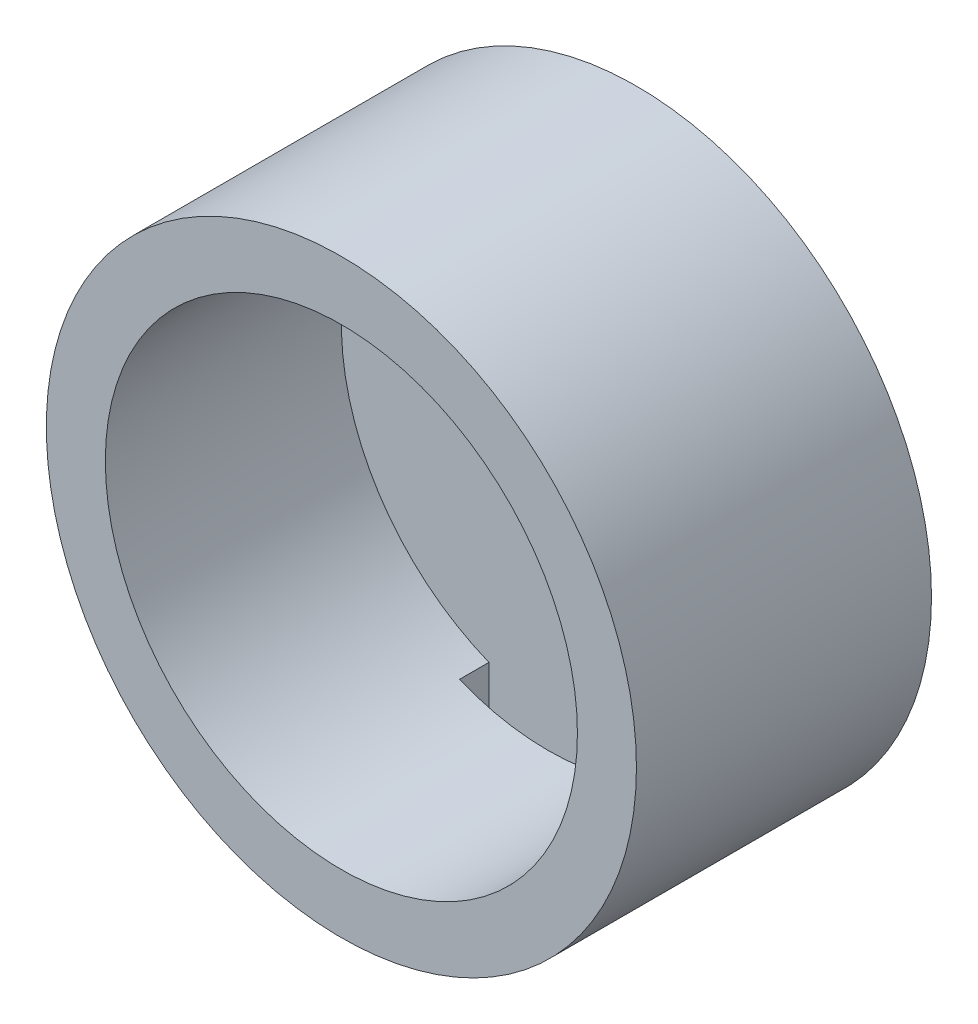
SolidWorks part; units mm, degrees
ref_plane "Top Plane" through (0, 0, 0) normal (0, 0, 1) x (1, 0, 0)
ref_plane "Front Plane" through (0, 0, 0) normal (0, 1, 0) x (1, 0, 0)
ref_plane "Right Plane" through (0, 0, 0) normal (1, 0, 0) x (0, 0, -1)
sketch "Sketch1" plane through (0, 0, 0) normal (0, 0, 1) x (1, 0, 0)
  circle A0 centre (0, 0) radius 50
extrude "Boss-Extrude1" add sketch "Sketch1" along normal blind 50
sketch "Sketch2" plane through (0, 0, 50) normal (0, 0, 1) x (1, 0, 0)
  circle A0 centre (0, 0) radius 40
extrude "Cut-Extrude1" cut sketch "Sketch2" against normal blind 40
sketch "Sketch3" plane through (0, 0, 0) normal (0, 1, 0) x (1, 0, 0)
  line L1 (-15, -15) -> (15, -15)
  line L2 (-15, -15) -> (-15, -10)
  line L3 (-15, -10) -> (15, -10)
  line L4 (15, -15) -> (15, -10)
  line L5 (50, -50) -> (50, 0) construction
  line L6 (50, 0) -> (-50, 0) construction
  dimension "D1" = 30
  dimension "D2" = 5
  dimension "D3" = 10
  dimension "D4" = 35
extrude "Cut-Extrude2" cut sketch "Sketch3" against normal blind 193
